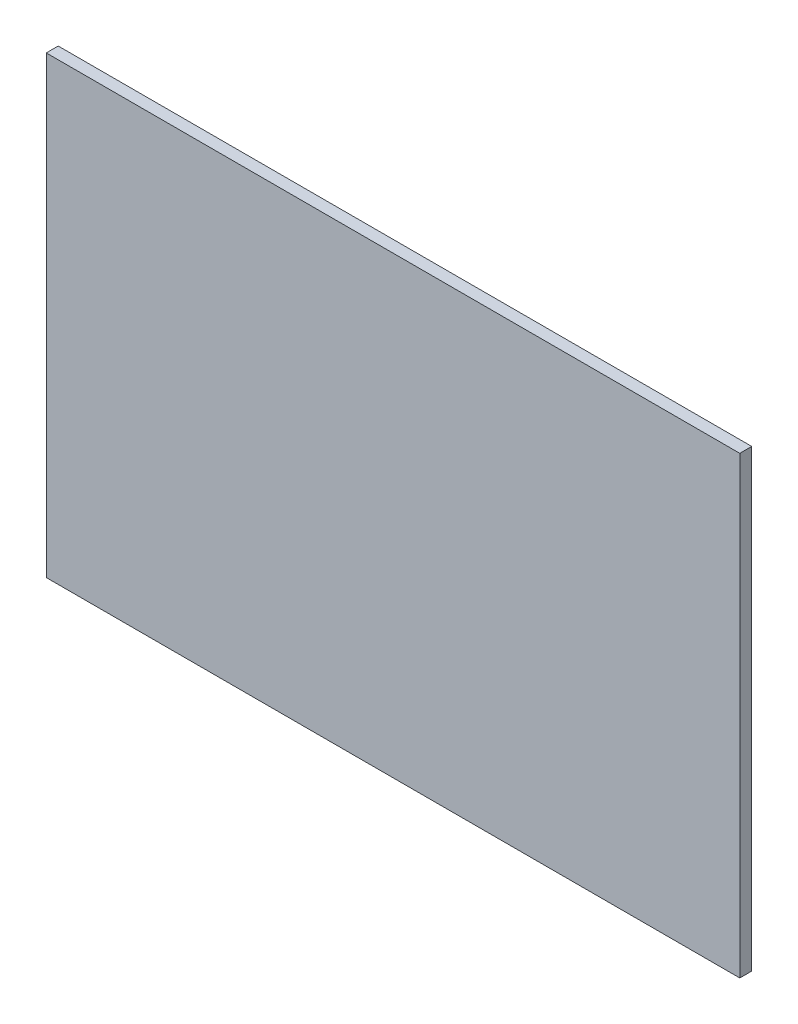
SolidWorks part; units mm, degrees
ref_plane "Спереди" through (0, 0, 0) normal (0, 0, 1) x (1, 0, 0)
ref_plane "Сверху" through (0, 0, 0) normal (0, 1, 0) x (1, 0, 0)
ref_plane "Справа" through (0, 0, 0) normal (1, 0, 0) x (0, 0, -1)
other "Configuration Table"
sketch "Эскиз1" plane through (0, 0, 0) normal (0, 0, 1) x (1, 0, 0)
  line L1 (145, 95) -> (-145, 95)
  line L2 (145, 95) -> (145, -95)
  line L3 (145, -95) -> (-145, -95)
  line L4 (-145, 95) -> (-145, -95)
  line L5 (145, 95) -> (-145, -95) construction
  line L6 (145, -95) -> (-145, 95) construction
  point P0 (0, 0)
  dimension "D1" = 190
  dimension "D2" = 290
extrude "Бобышка-Вытянуть1" add sketch "Эскиз1" along normal blind 5
